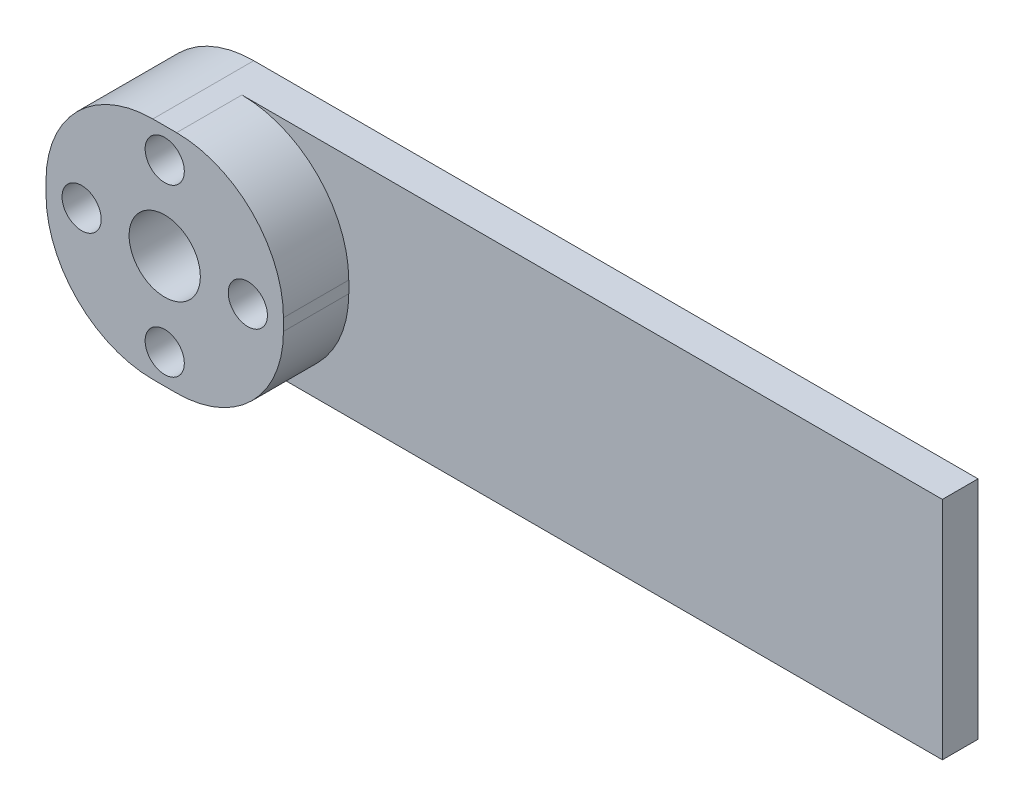
SolidWorks part; units mm, degrees
ref_plane "Front Plane" through (0, 0, 0) normal (0, 0, 1) x (1, 0, 0)
ref_plane "Top Plane" through (0, 0, 0) normal (0, 1, 0) x (1, 0, 0)
ref_plane "Right Plane" through (0, 0, 0) normal (1, 0, 0) x (0, 0, -1)
sketch "Sketch1" plane through (0, 0, 0) normal (0, 0, 1) x (1, 0, 0)
  line L1 (-10, 9.5) -> (60, 9.5)
  line L2 (-10, 9.5) -> (-10, -9.5)
  line L3 (-10, -9.5) -> (60, -9.5)
  line L4 (60, 9.5) -> (60, -9.5)
  line L5 (25, -9.5) -> (25, 9.5) construction
  line L6 (-10, 0) -> (60, 0) construction
  circle A0 centre (0, 0) radius 10
  circle A1 centre (0, 7) radius 1.65
  circle A2 centre (7, 0) radius 1.65
  circle A3 centre (0, -7) radius 1.65
  circle A4 centre (-7, 0) radius 1.65
  point P5 (25, 0)
  point P14 (0, 0)
  point P16 (0, 0)
  dimension "D1" = 20
  dimension "D2" = 7
  dimension "D3" = 3.3
  dimension "D6" = 10
  dimension "D5" = 70
  dimension "D7" = 19
  dimension "D4" = 4
extrude "Boss-Extrude1" add sketch "Sketch1" along normal blind 3 contours L4 L1 L2 L3 A0 | A0 A4 A3 A2 A1 | A0 L1 L2 | A0 L2 L3
sketch "Sketch2" plane through (0, 0, 3) normal (0, 0, 1) x (1, 0, 0)
  circle A0 centre (0, 0) radius 3
  dimension "D1" = 6
extrude "Cut-Extrude1" cut sketch "Sketch2" against normal blind 3
fillet "Fillet2" radius 9 2 edges at (-10, -9.5, 1.5) (-10, 9.5, 1.5)
sketch "Sketch3" plane through (0, 0, 3) normal (0, 0, 1) x (1, 0, 0)
  line L0 (-10, 0.5) -> (-10, -0.5) construction
  line L1 (-10, 0.5) -> (-10, -0.5)
  line L2 (-1, 9.5) -> (10, 9.5)
  line L3 (-1, 9.5) -> (60, 9.5) construction
  line L4 (10, 9.5) -> (10, -9.5)
  line L5 (-1, -9.5) -> (60, -9.5) construction
  line L6 (10, -9.5) -> (-1, -9.5)
  arc A0 (-10, -0.5) -> (-1, -9.5) centre (-1, -0.5) ccw construction
  arc A1 (-1, 9.5) -> (-10, 0.5) centre (-1, 0.5) ccw construction
  circle A2 centre (0, 7) radius 1.65 construction
  circle A3 centre (-7, 0) radius 1.65 construction
  circle A4 centre (0, -7) radius 1.65 construction
  circle A5 centre (0, 0) radius 3 construction
  circle A6 centre (7, 0) radius 1.65 construction
  arc A7 (-10, -0.5) -> (-1, -9.5) centre (-1, -0.5) ccw
  arc A8 (-1, 9.5) -> (-10, 0.5) centre (-1, 0.5) ccw
  circle A9 centre (0, 7) radius 1.65
  circle A10 centre (-7, 0) radius 1.65
  circle A11 centre (0, -7) radius 1.65
  circle A12 centre (0, 0) radius 3
  circle A13 centre (7, 0) radius 1.65
  dimension "D1" = 11
extrude "Boss-Extrude2" add sketch "Sketch3" along normal blind 5.5
fillet "Fillet3" radius 9 2 edges at (10, -9.5, 5.75) (10, 9.5, 5.75)
